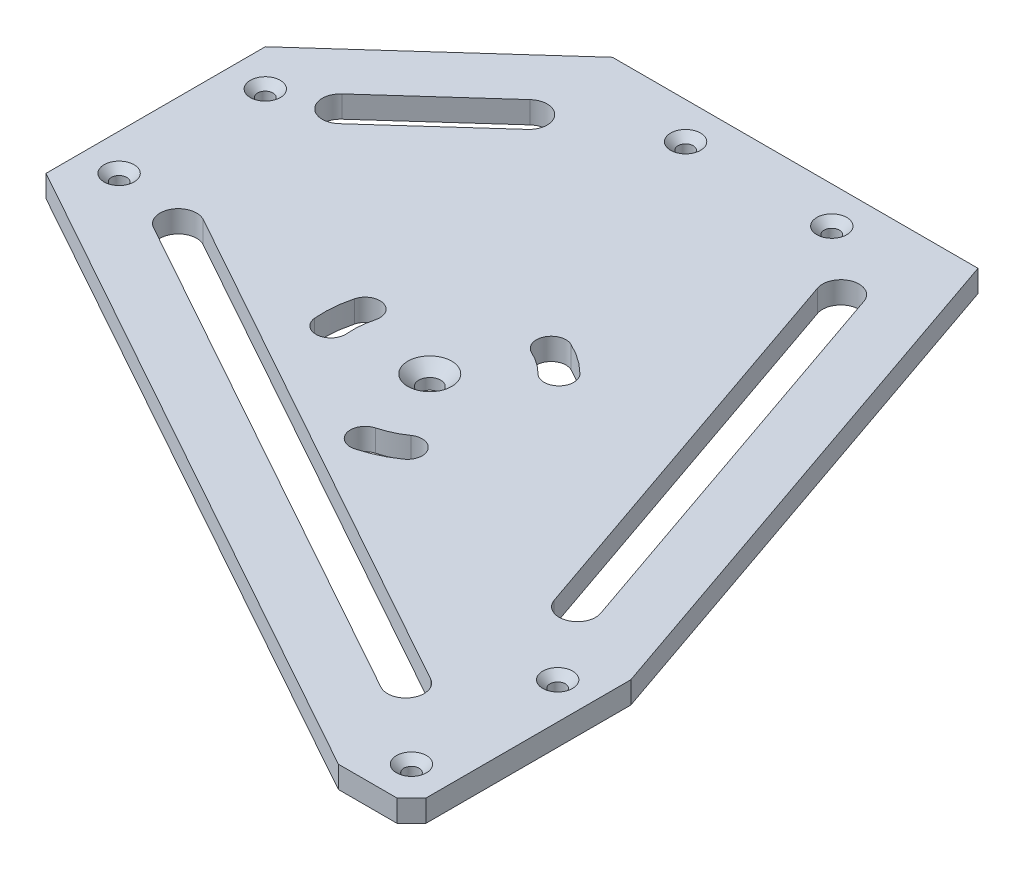
SolidWorks part; units mm, degrees
ref_plane "前视基准面" through (0, 0, 0) normal (0, 0, 1) x (1, 0, 0)
ref_plane "上视基准面" through (0, 0, 0) normal (0, 1, 0) x (1, 0, 0)
ref_plane "右视基准面" through (0, 0, 0) normal (1, 0, 0) x (0, 0, -1)
sketch "草图1" plane through (0, 0, 0) normal (0, 1, 0) x (1, 0, 0)
  line L0 (-50, 100) -> (50, 100)
  line L1 (50, 100) -> (100, -45)
  line L2 (100, -45) -> (100, -105)
  line L3 (100, -105) -> (-100, -5) construction
  line L4 (-100, -5) -> (-100, 55)
  line L5 (-100, 55) -> (-50, 100)
  line L6 (0, 100) -> (0, -55) construction
  line L7 (-90, 45) -> (-90, 5) construction
  line L8 (100, -105) -> (80, -105)
  line L9 (80, -105) -> (-100, -5)
  line L10 (90, -55) -> (90, -95) construction
  circle A0 centre (0, 0) radius 3
  circle A1 centre (-20, 90) radius 2.1
  circle A3 centre (-90, 45) radius 2.1
  circle A4 centre (-90, 5) radius 2.1
  circle A7 centre (20, 90) radius 2.1
  circle A8 centre (90, -55) radius 2.1
  circle A9 centre (90, -95) radius 2.1
  point P9 (0, 100)
  dimension "D1" = 200
  dimension "D6" = 6
  dimension "D7" = 10
  dimension "D8" = 10
  dimension "D9" = 4.2
  dimension "D5" = 5
  dimension "D12" = 40
  dimension "D14" = 10
  dimension "D15" = 205
  dimension "D2" = 100
  dimension "D3" = 10
  dimension "D4" = 100
  dimension "D10" = 40
  dimension "D11" = 10
  dimension "D13" = 20
  dimension "D16" = 10
extrude "凸台-拉伸1" add sketch "草图1" along normal mid plane 6
chamfer "倒角1" distance 2 angle 45 6 edges at (20, 3, -92.1) (-20, 3, -87.9) (90, 3, 97.1) (-90, 3, -42.9) (-90, 3, -2.9) (90, 3, 57.1)
chamfer "倒角3" distance 4 angle 45 1 edges at (100, 0, 105)
sketch "草图2" plane through (0, 3, 0) normal (0, 1, 0) x (1, 0, 0)
  line L0 (-75, 50.5928) -> (-47.8808, 75) construction
  line L1 (-78.3448, 54.3092) -> (-51.2257, 78.7165)
  line L2 (-71.6552, 46.8763) -> (-44.536, 71.2835)
  line L3 (-50, 100) -> (-100, 55) construction
  line L5 (50, 100) -> (-50, 100) construction
  line L6 (75.3961, -35) -> (37.465, 75) construction
  line L7 (70.6692, -36.63) -> (32.7382, 73.37)
  line L8 (80.1229, -33.37) -> (42.1919, 76.63)
  line L9 (100, -45) -> (50, 100) construction
  line L10 (70, -76.5653) -> (-70, 1.2125) construction
  line L11 (67.5718, -80.9361) -> (-72.4282, -3.1583)
  line L12 (72.4282, -72.1945) -> (-67.5718, 5.5833)
  line L13 (-100, -5) -> (80, -105) construction
  arc A0 (-78.3448, 54.3092) -> (-71.6552, 46.8763) centre (-75, 50.5928) ccw
  arc A1 (-44.536, 71.2835) -> (-51.2257, 78.7165) centre (-47.8808, 75) ccw
  arc A2 (70.6692, -36.63) -> (80.1229, -33.37) centre (75.3961, -35) ccw
  arc A3 (42.1919, 76.63) -> (32.7382, 73.37) centre (37.465, 75) ccw
  arc A6 (67.5718, -80.9361) -> (72.4282, -72.1945) centre (70, -76.5653) ccw
  arc A7 (-67.5718, 5.5833) -> (-72.4282, -3.1583) centre (-70, 1.2125) ccw
  circle A8 centre (-90, 5) radius 4.1 construction
  circle A9 centre (90, -95) radius 4.1 construction
  circle A10 centre (-90, 45) radius 4.1 construction
  circle A11 centre (-20, 90) radius 4.1 construction
  point P2 (-61.4404, 62.7964)
  point P12 (56.4305, 20)
  point P28 (0, -37.6764)
  dimension "D3" = 5
  dimension "D6" = 25
  dimension "D7" = 10
  dimension "D4" = 15
  dimension "D8" = 20
  dimension "D10" = 20
  dimension "D11" = 15
  dimension "D2" = 15
  dimension "D5" = 15
  dimension "D9" = 15
extrude "切除-拉伸1" cut sketch "草图2" against normal through all
chamfer "倒角4" distance 3 angle 45 1 edges at (0, 3, 3)
sketch "草图3" plane through (0, 3, 0) normal (0, 1, 0) x (1, 0, 0)
  line L0 (17.6777, 17.6777) -> (0, 0) construction
  line L1 (50, 100) -> (-50, 100) construction
  arc A0 (17.6777, 17.6777) -> (10.5655, 22.6577) centre (0, 0) ccw construction
  arc A1 (20.5415, 20.5415) -> (12.2771, 26.3282) centre (0, 0) ccw
  arc A2 (14.8139, 14.8139) -> (8.8539, 18.9871) centre (0, 0) ccw
  arc A3 (14.8139, 14.8139) -> (20.5415, 20.5415) centre (17.6777, 17.6777) ccw
  arc A4 (12.2771, 26.3282) -> (8.8539, 18.9871) centre (10.5655, 22.6577) ccw
  point P4 (14.3394, 20.4788)
  dimension "D1" = 25
  dimension "D2" = 4.05
  dimension "D3" = 20
  dimension "D4" = 45
extrude "切除-拉伸2" cut sketch "草图3" against normal through all
pattern_circular "阵列(圆周)1" count 3 over 360 about axis through (0, 0, 0) along (0, 1, 0) of "切除-拉伸2"
